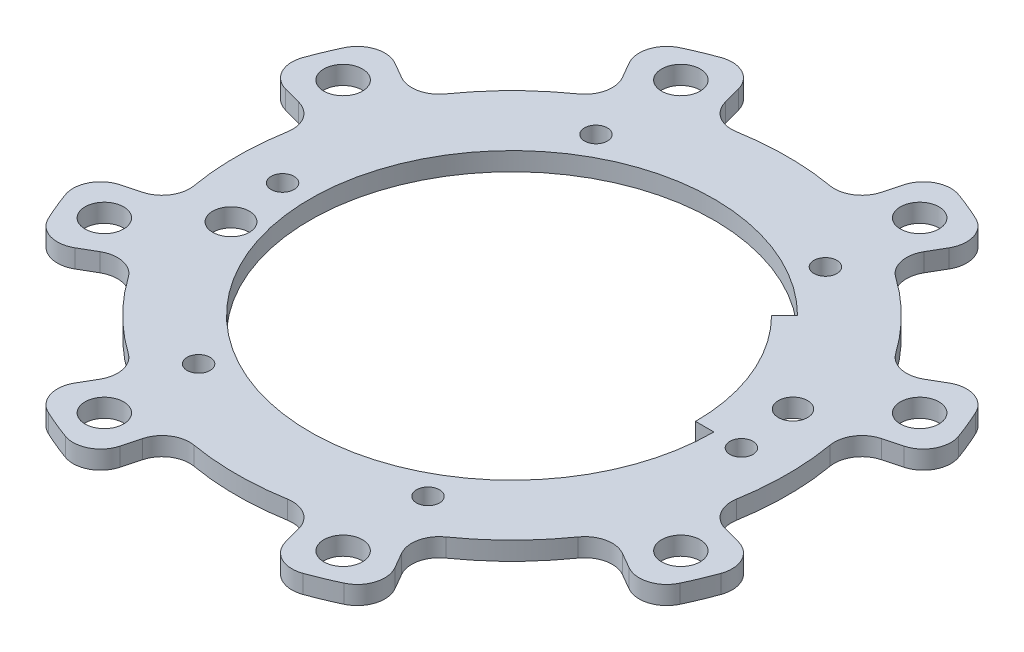
SolidWorks part; units mm, degrees
material "A-玻璃纤维"
ref_plane "前视基准面" through (0, 0, 0) normal (0, 0, 1) x (1, 0, 0)
ref_plane "上视基准面" through (0, 0, 0) normal (0, 1, 0) x (1, 0, 0)
ref_plane "右视基准面" through (0, 0, 0) normal (1, 0, 0) x (0, 0, -1)
other "Configuration Table"
sketch "草图1" plane through (0, 0, 0) normal (0, 1, 0) x (1, 0, 0)
  circle A0 centre (0, 0) radius 38
  circle A1 centre (0, 0) radius 34 construction
  circle A2 centre (0, 0) radius 22
  dimension "D1" = 76
  dimension "D2" = 68
  dimension "D3" = 44
extrude "凸台-拉伸1" add sketch "草图1" along normal blind 2
sketch "草图2" plane through (0, 2, 0) normal (0, 1, 0) x (1, 0, 0)
  line L0 (0, 0) -> (13.0112, 31.4119) construction
  circle A0 centre (0, 0) radius 34 construction
  circle A1 centre (13.0112, 31.4119) radius 2.1
  circle A2 centre (31.4119, 13.0112) radius 2.1
  circle A3 centre (31.4119, -13.0112) radius 2.1
  circle A4 centre (13.0112, -31.4119) radius 2.1
  circle A5 centre (-13.0112, -31.4119) radius 2.1
  circle A6 centre (-31.4119, -13.0112) radius 2.1
  circle A7 centre (-31.4119, 13.0112) radius 2.1
  circle A8 centre (-13.0112, 31.4119) radius 2.1
  dimension "D1" = 68
  dimension "D2" = 4.2
  dimension "D4" = 34
  dimension "D3" = 8
extrude "切除-拉伸1" cut sketch "草图2" against normal through all
sketch "草图3" plane through (0, 2, 0) normal (0, 1, 0) x (1, 0, 0)
  line L0 (0, 0) -> (12.5, 21.6506) construction
  circle A0 centre (0, 0) radius 25 construction
  circle A1 centre (12.5, 21.6506) radius 1.25
  circle A2 centre (25, 0) radius 1.25
  circle A3 centre (12.5, -21.6506) radius 1.25
  circle A4 centre (-12.5, -21.6506) radius 1.25
  circle A5 centre (-25, 0) radius 1.25
  circle A6 centre (-12.5, 21.6506) radius 1.25
  dimension "D1" = 50
  dimension "D2" = 2.5
  dimension "D4" = 25
  dimension "D3" = 6
extrude "切除-拉伸2" cut sketch "草图3" against normal through all
sketch "草图5" plane through (0, 2, 0) normal (0, 1, 0) x (1, 0, 0)
  line L0 (-24.1481, -6.4705) -> (24.1481, 6.4705) construction
  line L1 (-25, 0) -> (25, 0) construction
  circle A0 centre (0, 0) radius 25 construction
  circle A1 centre (24.1481, 6.4705) radius 1.6
  circle A2 centre (-24.1481, -6.4705) radius 2
  dimension "D2" = 4
  dimension "D3" = 3.2
  dimension "D1" = 15
extrude "切除-拉伸3" cut sketch "草图5" against normal through all
sketch "草图6" plane through (0, 2, 0) normal (0, 1, 0) x (1, 0, 0)
  line L0 (0, 38) -> (0, 0) construction
  line L1 (0, 0) -> (-9.8351, 36.7052)
  line L2 (9.8351, 36.7052) -> (0, 0)
  line L3 (0, 0) -> (19, 32.909)
  line L4 (32.909, 19) -> (0, 0)
  line L5 (0, 0) -> (36.7052, 9.8351)
  line L6 (36.7052, -9.8351) -> (0, 0)
  line L7 (0, 0) -> (32.909, -19)
  line L8 (19, -32.909) -> (0, 0)
  line L9 (0, 0) -> (9.8351, -36.7052)
  line L10 (-9.8351, -36.7052) -> (0, 0)
  line L11 (0, 0) -> (-19, -32.909)
  line L12 (-32.909, -19) -> (0, 0)
  line L14 (0, 0) -> (-36.7052, -9.8351)
  line L15 (-36.7052, 9.8351) -> (0, 0)
  line L16 (0, 0) -> (-32.909, 19)
  line L17 (-19, 32.909) -> (0, 0)
  circle A0 centre (0, 0) radius 30
  circle A1 centre (0, 0) radius 38 construction
  circle M21 centre (0, 0) radius 38
  dimension "D1" = 60
  dimension "D2" = 15
  dimension "D3" = 15
  dimension "D4" = 8
extrude "切除-拉伸4" cut sketch "草图6" against normal through all contours A0 L17 L16 M21 | L0 A0 L2 M21 | L0 L1 A0 M21 | A0 L4 L3 M21 | A0 L6 L5 M21 | A0 L8 L7 M21 | A0 L10 L9 M21 | A0 L12 L11 M21 | A0 L15 L14 M21
fillet "圆角1" radius 3 32 edges at (7.7646, 1, -28.9778) (-7.7646, 1, -28.9778) (-9.8351, 1, -36.7052) (-15, 1, -25.9808) (-25.9808, 1, -15) (-32.909, 1, -19) (-36.7052, 1, -9.8351) (-28.9778, 1, -7.7646) (-28.9778, 1, 7.7646) (-36.7052, 1, 9.8351) (-32.909, 1, 19) (-25.9808, 1, 15) (-15, 1, 25.9808) (-19, 1, 32.909) (-9.8351, 1, 36.7052) (-7.7646, 1, 28.9778) (7.7646, 1, 28.9778) (9.8351, 1, 36.7052) (19, 1, 32.909) (15, 1, 25.9808) (25.9808, 1, 15) (32.909, 1, 19) (36.7052, 1, 9.8351) (28.9778, 1, 7.7646) (28.9778, 1, -7.7646) (36.7052, 1, -9.8351) (32.909, 1, -19) (25.9808, 1, -15) (15, 1, -25.9808) (19, 1, -32.909) (9.8351, 1, -36.7052) (-19, 1, -32.909)
sketch "草图7" plane through (0, 0, 0) normal (0, -1, 0) x (1, 0, 0)
  line L0 (0, 0) -> (31.4119, -13.0112) construction
  line L1 (30, 0) -> (0, 0) construction
  line L2 (0, 0) -> (21.2132, -21.2132) construction
  line L3 (22, 0) -> (20, 0)
  line L4 (14.1421, -14.1421) -> (15.5563, -15.5563)
  arc A0 (29.5637, -5.0981) -> (29.5637, 5.0981) centre (0, 0) ccw construction
  arc A2 (17.2998, -24.5095) -> (24.5095, -17.2998) centre (0, 0) ccw construction
  circle A3 centre (31.4119, -13.0112) radius 2.1 construction
  arc A4 (15.5563, -15.5563) -> (22, 0) centre (0, 0) ccw
  arc A5 (14.1421, -14.1421) -> (20, 0) centre (0, 0) ccw
  dimension "D1" = 20
  dimension "D2" = 22
extrude "凸台-拉伸2" add sketch "草图7" against normal up to surface (2 mm away) up to face at (-24.1481, 2, 8.4705)
